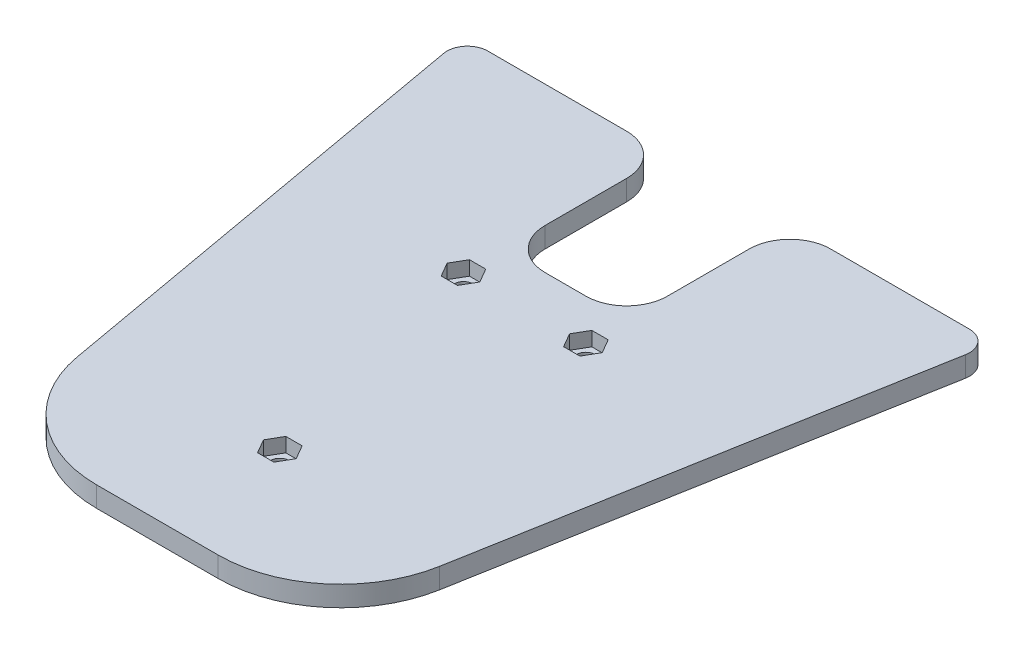
SolidWorks part; units mm, degrees
ref_plane "Front Plane" through (0, 0, 0) normal (0, 0, 1) x (1, 0, 0)
ref_plane "Top Plane" through (0, 0, 0) normal (0, 1, 0) x (1, 0, 0)
ref_plane "Right Plane" through (0, 0, 0) normal (1, 0, 0) x (0, 0, -1)
sketch "Sketch1" plane through (0, 0, 0) normal (0, 1, 0) x (1, 0, 0)
  line L0 (-15, 40) -> (-15, 80)
  line L1 (-15, 40) -> (15, 40)
  line L2 (-15, 80) -> (-65, 80)
  line L3 (-65, 80) -> (-40, -60)
  line L4 (65, 80) -> (40, -60)
  line L5 (0, -60) -> (40, -60)
  line L8 (15, 40) -> (15, 80)
  line L9 (15, 80) -> (65, 80)
  line L13 (-40, -60) -> (0, -60)
extrude "Boss-Extrude1" add sketch "Sketch1" along normal blind 5
sketch "Sketch2" plane through (0, 5, 0) normal (0, 1, 0) x (1, 0, 0)
  circle A0 centre (0, -30) radius 2.25
  circle A1 centre (-15, 30) radius 2.25
  circle A2 centre (15, 30) radius 2.25
  point P4 (-15, 29.2703)
  point P12 (0, 0)
  point P13 (15, 29.1584)
extrude "Cut-Extrude1" cut sketch "Sketch2" against normal blind 5
fillet "Fillet7" radius 30 1 edges at (-40, 2.5, 60)
fillet "Fillet8" radius 30 1 edges at (40, 2.5, 60)
fillet "Fillet9" radius 10 1 edges at (15, 2.5, -80)
fillet "Fillet10" radius 10 1 edges at (-15, 2.5, -80)
fillet "Fillet11" radius 10 1 edges at (15, 2.5, -40)
fillet "Fillet12" radius 10 1 edges at (-15, 2.5, -40)
fillet "Fillet13" radius 5 1 edges at (65, 2.5, -80)
fillet "Fillet14" radius 5 1 edges at (-65, 2.5, -80)
sketch "Sketch3" plane through (0, 5, 0) normal (0, 1, 0) x (1, 0, 0)
  line L1 (-4, -30) -> (-2, -33.4641)
  line L2 (4, -30) -> (2, -26.5359)
  line L3 (2, -26.5359) -> (-2, -26.5359)
  line L4 (-2, -26.5359) -> (-4, -30)
  line L5 (-2, -33.4641) -> (2, -33.4641)
  line L6 (2, -33.4641) -> (4, -30)
  line L11 (-11, 30) -> (-13, 33.4641)
  line L12 (-13, 33.4641) -> (-17, 33.4641)
  line L13 (-17, 33.4641) -> (-19, 30)
  line L14 (-19, 30) -> (-17, 26.5359)
  line L15 (-17, 26.5359) -> (-13, 26.5359)
  line L16 (-13, 26.5359) -> (-11, 30)
  line L17 (19, 30) -> (17, 33.4641)
  line L18 (17, 33.4641) -> (13, 33.4641)
  line L19 (13, 33.4641) -> (11, 30)
  line L20 (11, 30) -> (13, 26.5359)
  line L21 (13, 26.5359) -> (17, 26.5359)
  line L22 (17, 26.5359) -> (19, 30)
  circle A0 centre (0, -30) radius 4.8463 construction
  circle A1 centre (-15, 30) radius 4 construction
  circle A2 centre (15, 30) radius 4 construction
extrude "Cut-Extrude2" cut sketch "Sketch3" against normal blind 3.5
